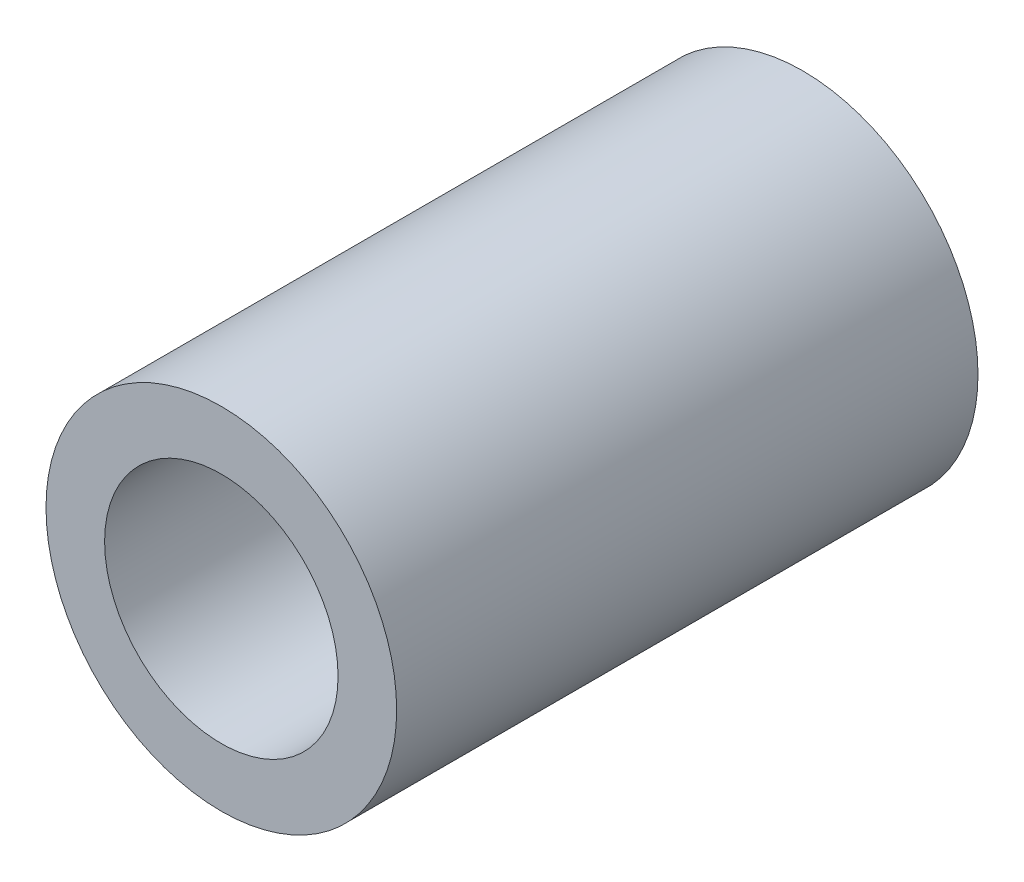
SolidWorks part; units mm, degrees
ref_plane "Front Plane" through (0, 0, 0) normal (0, 0, 1) x (1, 0, 0)
ref_plane "Top Plane" through (0, 0, 0) normal (0, 1, 0) x (1, 0, 0)
ref_plane "Right Plane" through (0, 0, 0) normal (1, 0, 0) x (0, 0, -1)
sketch "Sketch1" plane through (0, 0, 0) normal (0, 0, 1) x (1, 0, 0)
  circle A0 centre (0, 0) radius 4.7879
  circle A1 centre (0, 0) radius 3.1877
  dimension "D1" = 9.5758
  dimension "ID" = 6.3754
extrude "Extrude1" add sketch "Sketch1" along normal mid plane 15.875
sketch "Sketch2" plane through (0, 0, 0) normal (1, 0, 0) x (0, 0, -1)
  line L0 (-7.9375, -3.1877) -> (7.9375, -3.1877) construction
  line L3 (7.9375, 3.1877) -> (-7.9375, 3.1877) construction
  line L5 (-7.9375, -3.1877) -> (7.9375, -3.1877)
  line L6 (7.9375, 3.1877) -> (-7.9375, 3.1877)
sketch "Sketch4" plane through (0, 0, 7.9375) normal (0, 0, 1) x (1, 0, 0)
  line L0 (0, 0) -> (-2.254, 2.254)
  line L1 (0, -13.97) -> (0, 13.97) construction
  circle A0 centre (0, 0) radius 3.1877 construction
  dimension "D1" = 45
